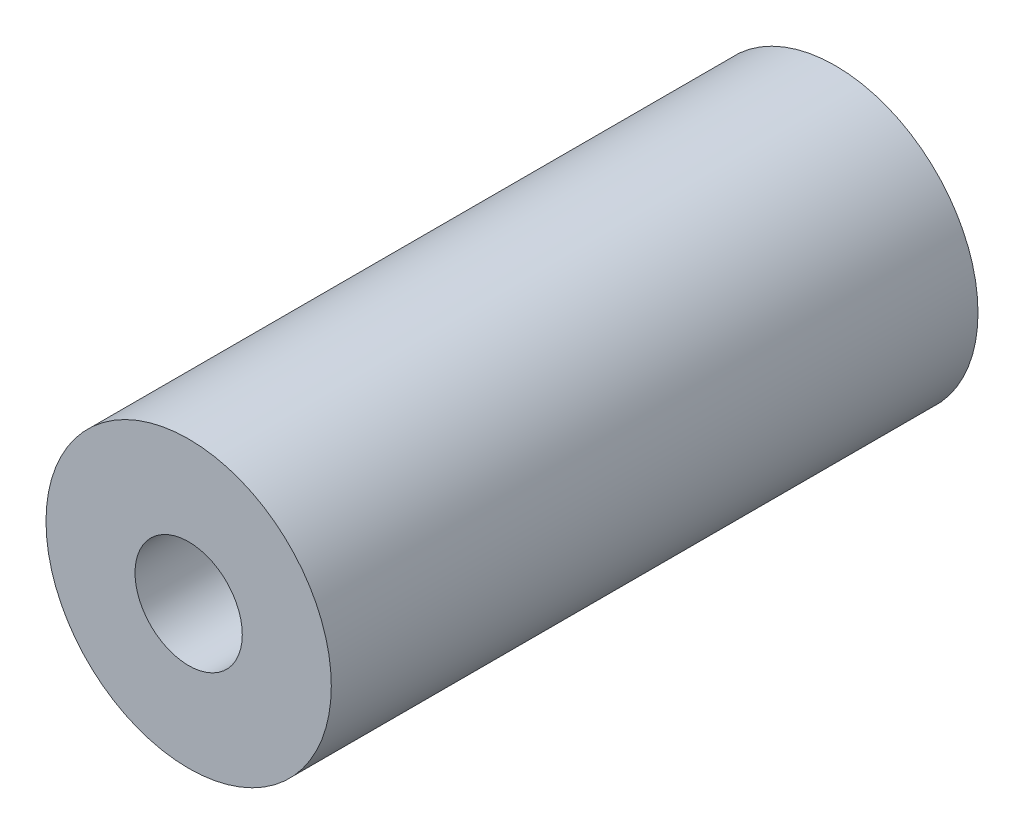
SolidWorks part; units mm, degrees
ref_plane "Front Plane" through (0, 0, 0) normal (0, 0, 1) x (1, 0, 0)
ref_plane "Top Plane" through (0, 0, 0) normal (0, 1, 0) x (1, 0, 0)
ref_plane "Right Plane" through (0, 0, 0) normal (1, 0, 0) x (0, 0, -1)
sketch "Sketch1" plane through (0, 0, 0) normal (0, 0, 1) x (1, 0, 0)
  circle A0 centre (0, 0) radius 3.75
  circle A1 centre (0, 0) radius 1.41
  dimension "D1" = 7.5
  dimension "D2" = 2.82
extrude "Boss-Extrude1" add sketch "Sketch1" along normal blind 17
